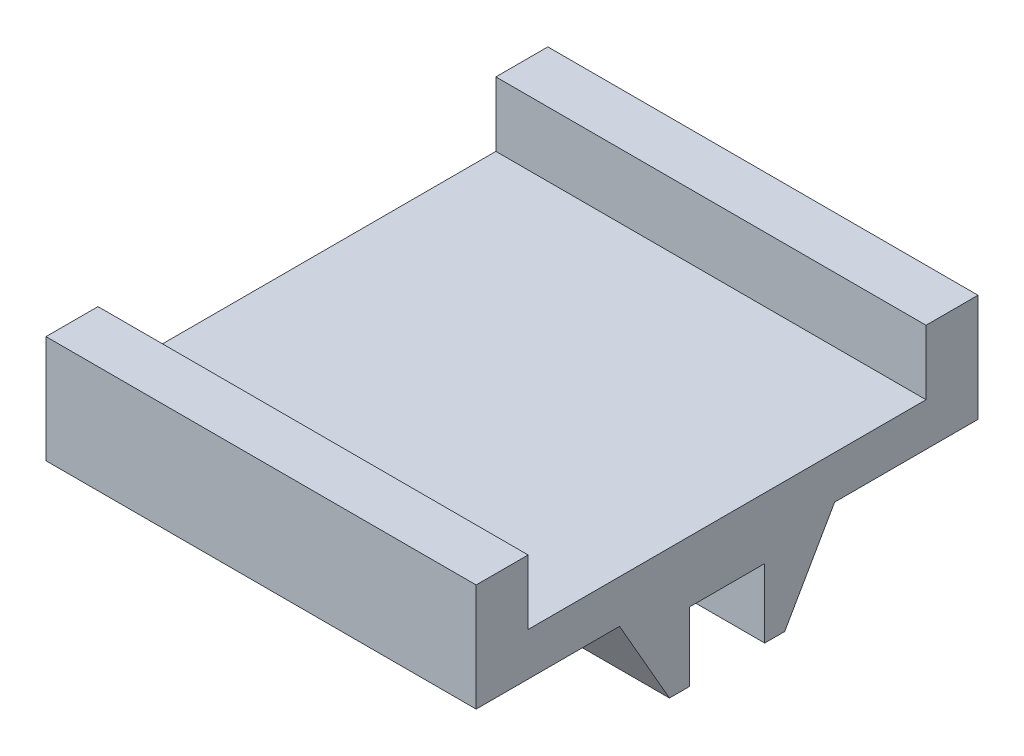
SolidWorks part; units mm, degrees
ref_plane "前视基准面" through (0, 0, 0) normal (0, 0, 1) x (1, 0, 0)
ref_plane "上视基准面" through (0, 0, 0) normal (0, 1, 0) x (1, 0, 0)
ref_plane "右视基准面" through (0, 0, 0) normal (1, 0, 0) x (0, 0, -1)
sketch "草图2" plane through (0, 0, 0) normal (0, 1, 0) x (1, 0, 0)
  line L0 (-34.4528, 66.1118) -> (-34.4528, -3.8882)
  line L1 (-34.4528, -3.8882) -> (25.5472, -3.8882)
  line L2 (25.5472, -3.8882) -> (25.5472, 66.1118)
  line L3 (25.5472, 66.1118) -> (-34.4528, 66.1118)
  dimension "D1" = 60
  dimension "D2" = 70
extrude "凸台-拉伸1" add sketch "草图2" along normal blind 15
sketch "草图7" plane through (-34.4528, 0, 0) normal (-1, 0, 0) x (0, 0, 1)
  line L0 (-58.8618, 15) -> (-58.8618, 6)
  line L1 (-66.1118, 15) -> (3.8882, 15) construction
  line L2 (-58.8618, 6) -> (-3.3618, 6)
  line L3 (-3.3618, 6) -> (-3.3618, 15)
  line L4 (-3.3618, 15) -> (-58.8618, 15)
  line L6 (-66.1118, 15) -> (-66.1118, 0) construction
  line L7 (-66.1118, 0) -> (3.8882, 0) construction
  dimension "D1" = 55.5
  dimension "D2" = 7.25
  dimension "D3" = 6
extrude "切除-拉伸3" cut sketch "草图7" against normal through all
sketch "草图8" plane through (-34.4528, 0, 0) normal (-1, 0, 0) x (0, 0, 1)
  line L0 (-46.1118, 0) -> (-16.1118, 0)
  line L1 (-66.1118, 0) -> (3.8882, 0) construction
  line L2 (-16.1118, 0) -> (-23.0768, -12.1445)
  line L4 (-39.1468, -12.1445) -> (-46.1118, 0)
  line L5 (-39.1468, -12.1445) -> (-36.3618, -12.1445)
  line L6 (-39.1468, 0) -> (-39.1468, -12.1445) construction
  line L7 (-66.1118, 15) -> (-66.1118, 0) construction
  line L8 (-36.3618, -12.1445) -> (-36.3618, -2.5374)
  line L9 (-36.3618, -2.5374) -> (-25.8618, -2.5374)
  line L10 (-25.8618, -2.5374) -> (-25.8618, -12.1445)
  line L12 (-25.8618, -12.1445) -> (-23.0768, -12.1445)
  dimension "D1" = 30
  dimension "D2" = 16.07
  dimension "D3" = 14
  dimension "D4" = 14
  dimension "D5" = 26.965
  dimension "D6" = 10.5
  dimension "D7" = 2.785
extrude "凸台-拉伸3" add sketch "草图8" against normal blind 60
